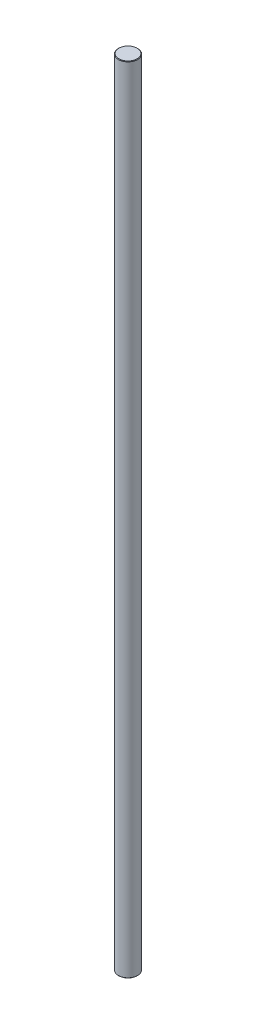
SolidWorks part; units mm, degrees
material "Plain Carbon Steel"
ref_plane "Front Plane" through (0, 0, 0) normal (0, 0, 1) x (1, 0, 0)
ref_plane "Top Plane" through (0, 0, 0) normal (0, 1, 0) x (1, 0, 0)
ref_plane "Right Plane" through (0, 0, 0) normal (1, 0, 0) x (0, 0, -1)
sketch "Sketch1" plane through (0, 0, 0) normal (0, 1, 0) x (1, 0, 0)
  circle A0 centre (0, 0) radius 4
  dimension "D1" = 8
extrude "Boss-Extrude1" add sketch "Sketch1" along normal blind 330
chamfer "Chamfer1" distance 0.2 angle 45 2 edges at (0, 0, 4) (0, 330, 4)
